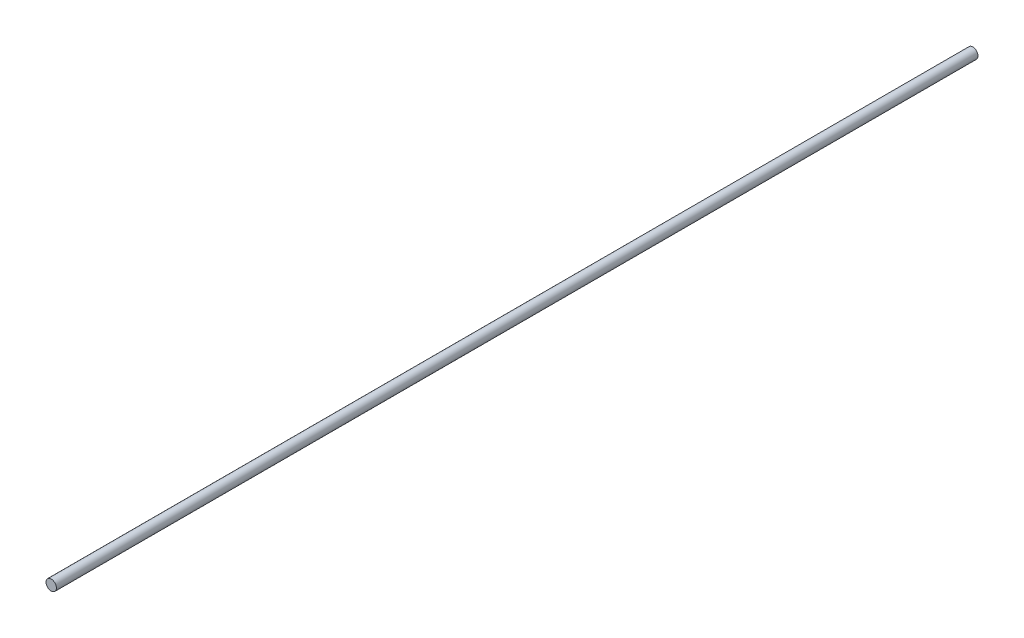
SolidWorks part; units mm, degrees
material "1060 Alloy"
ref_plane "Front Plane" through (0, 0, 0) normal (0, 0, 1) x (1, 0, 0)
ref_plane "Top Plane" through (0, 0, 0) normal (0, 1, 0) x (1, 0, 0)
ref_plane "Right Plane" through (0, 0, 0) normal (1, 0, 0) x (0, 0, -1)
sketch "Sketch1" plane through (0, 0, 0) normal (0, 0, 1) x (1, 0, 0)
  circle A0 centre (0, 0) radius 6.35
  dimension "D1" = 12.7
extrude "Boss-Extrude1" add sketch "Sketch1" against normal blind 1122.1376
equation "\"F\"= 400"
equation "\"E\"= 10000000"
equation "\"Deflection\"= 0.009"
equation "\"Diameter\"= 0.5"
equation "\"Area\"= PI * \"Diameter\" ^ 2 / 4"
equation "\"Length\"= \"Deflection\" * \"Area\" * \"E\" / \"F\""
equation "\"D1@Sketch1\"=\"Diameter\""
equation "\"D1@Boss-Extrude1\"=\"Length\""
